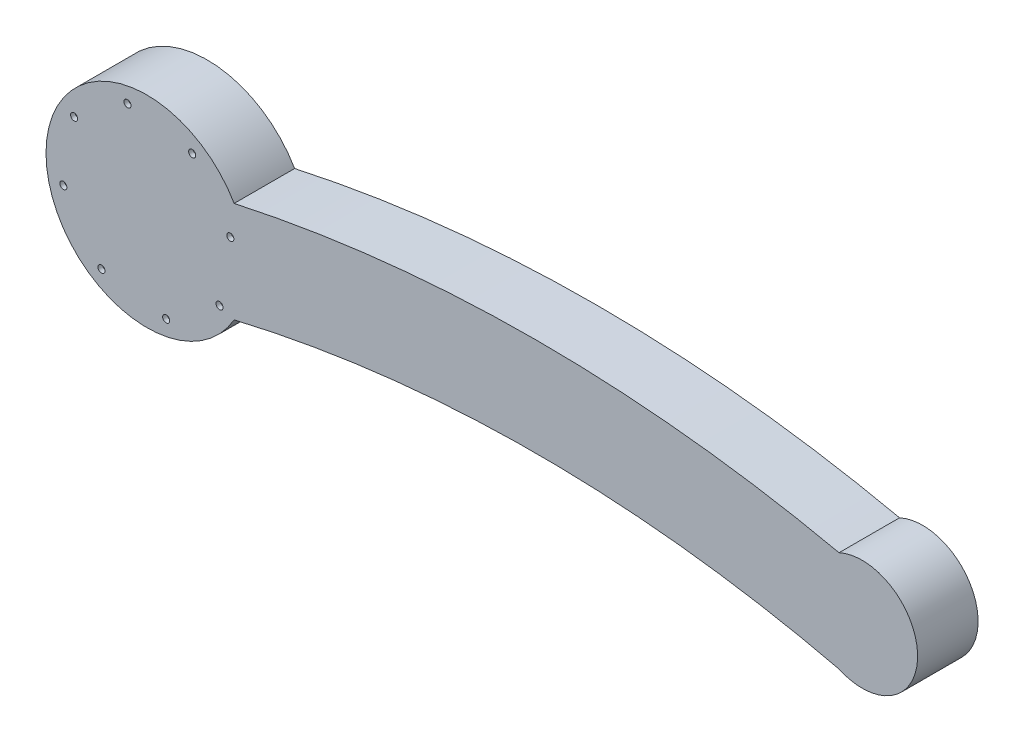
SolidWorks part; units mm, degrees
ref_plane "前视基准面" through (0, 0, 0) normal (0, 0, 1) x (1, 0, 0)
ref_plane "上视基准面" through (0, 0, 0) normal (0, 1, 0) x (1, 0, 0)
ref_plane "右视基准面" through (0, 0, 0) normal (1, 0, 0) x (0, 0, -1)
sketch "草图1" plane through (0, 0, 0) normal (0, 0, 1) x (1, 0, 0)
  line L1 (-150, 25) -> (150, 25)
  line L2 (-150, 25) -> (-150, -25)
  line L3 (-150, -25) -> (150, -25)
  line L4 (150, 25) -> (150, -25)
  line L5 (-150, 25) -> (150, -25) construction
  line L6 (-150, -25) -> (150, 25) construction
  arc A0 (-150, -25) -> (150, -25) centre (0, -657.4555) cw
  arc A1 (-150, 25) -> (150, 25) centre (0, -658.7397) cw
  circle A2 centre (161.4564, 0) radius 27.5
  circle A3 centre (-193.3013, 0) radius 50
  point P0 (0, 0)
  dimension "D3" = 50
  dimension "D4" = 650
  dimension "D5" = 700
  dimension "D6" = 55
  dimension "D7" = 100
  dimension "D1" = 300
  dimension "D2" = 50
extrude "凸台-拉伸3" add sketch "草图1" along normal blind 30 contours L4 A2 | L4 A2 | A3 A0 A2 L1 | A1 L1 | L2 A3 | L2 A3
sketch "草图3" plane through (0, 0, 0) normal (0, 0, -1) x (-1, 0, 0)
  line L0 (148.2429, 10.4311) -> (238.3596, -10.4311)
  line L1 (151.1094, 23.4074) -> (145.1153, -2.4848)
  line L2 (241.4602, 2.9624) -> (235.259, -23.8246)
  circle A0 centre (193.3013, 0) radius 48.25
  arc A4 (-150, 25) -> (-150, -25) centre (-161.4564, 0) ccw
  arc A5 (150, -25) -> (-150, -25) centre (0, -657.4555) ccw
  arc A6 (150, -25) -> (150, 25) centre (193.3013, 0) ccw
  arc A7 (150, 25) -> (-150, 25) centre (0, -658.7397) ccw
  arc A8 (-150, 25) -> (-150, -25) centre (-161.4564, 0) ccw
  arc A9 (150, -25) -> (-150, -25) centre (0, -657.4555) ccw
  arc A10 (150, -25) -> (150, 25) centre (193.3013, 0) ccw
  arc A11 (150, 25) -> (-150, 25) centre (0, -658.7397) ccw
  point P9 (193.3013, 0)
  point P16 (238.3596, -10.4311)
  point P17 (0, 0)
  dimension "D2" = 96.5
  dimension "D3" = 92.5
  dimension "D4" = 90.1167
  dimension "D5" = 25.8922
  dimension "D1" = 0
extrude "切除-拉伸1" cut sketch "草图3" against normal blind 27.75
sketch "草图5" plane through (0, 0, 27.75) normal (0, 0, -1) x (-1, 0, 0)
  line L0 (148.1123, 10.4613) -> (193.3013, 0) construction
  line L2 (235.259, -23.8246) -> (241.4602, 2.9624)
  line L3 (151.1094, 23.4074) -> (145.1153, -2.4848)
  line L4 (235.259, -23.8246) -> (241.4602, 2.9624)
  line L5 (151.1094, 23.4074) -> (145.1153, -2.4848)
  circle A0 centre (193.3013, 0) radius 42.5 construction
  circle A1 centre (151.8963, 9.5853) radius 1.75
  arc A2 (145.1153, -2.4848) -> (235.259, -23.8246) centre (193.3013, 0) ccw
  arc A3 (241.4602, 2.9624) -> (151.1094, 23.4074) centre (193.3013, 0) ccw
  arc A4 (145.1153, -2.4848) -> (235.259, -23.8246) centre (193.3013, 0) ccw
  arc A5 (241.4602, 2.9624) -> (151.1094, 23.4074) centre (193.3013, 0) ccw
  circle A6 centre (170.8014, 36.0556) radius 1.75
  circle A7 centre (202.8866, 41.405) radius 1.75
  circle A8 centre (229.3569, 22.4999) radius 1.75
  circle A9 centre (234.7062, -9.5853) radius 1.75
  circle A10 centre (215.8012, -36.0556) radius 1.75
  circle A11 centre (183.7159, -41.405) radius 1.75
  circle A12 centre (157.2457, -22.4999) radius 1.75
  point P27 (193.3013, 0)
  dimension "D2" = 85
  dimension "D3" = 3.5
  dimension "D1" = 0
  dimension "D4" = 8
extrude "切除-拉伸2" cut sketch "草图5" against normal through all contours A1 | A12 | A11 | A10 | A9 | A8 | A7 | A6
